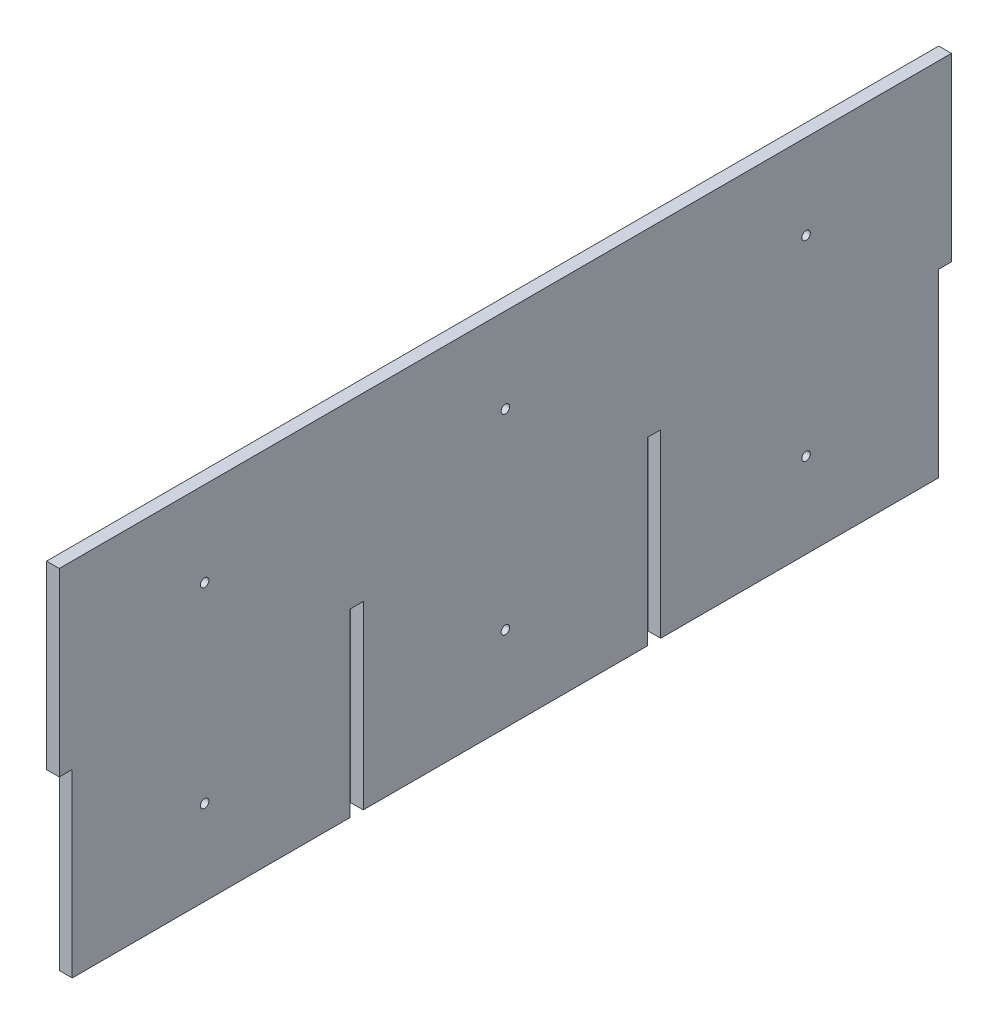
SolidWorks part; units mm, degrees
ref_plane "Front Plane" through (0, 0, 0) normal (0, 0, 1) x (1, 0, 0)
ref_plane "Top Plane" through (0, 0, 0) normal (0, 1, 0) x (1, 0, 0)
ref_plane "Right Plane" through (0, 0, 0) normal (1, 0, 0) x (0, 0, -1)
sketch "Sketch3" plane through (0, 0, 0) normal (1, 0, 0) x (0, 0, -1)
  line L1 (230.9117, 76.9159) -> (650.9117, 76.9159)
  line L2 (230.9117, 76.9159) -> (230.9117, 246.9159)
  line L3 (230.9117, 246.9159) -> (650.9117, 246.9159)
  line L4 (650.9117, 76.9159) -> (650.9117, 246.9159)
  dimension "D1" = 170
  dimension "D2" = 420
extrude "Boss-Extrude2" add sketch "Sketch3" along normal blind 6
sketch "Sketch4" plane through (6, 0, 0) normal (1, 0, 0) x (0, 0, -1)
  line L0 (230.9117, 246.9159) -> (230.9117, 76.9159) construction
  line L1 (230.9117, 161.9159) -> (237.0117, 161.9159)
  line L2 (230.9117, 161.9159) -> (230.9117, 76.9159)
  line L3 (230.9117, 76.9159) -> (237.0117, 76.9159)
  line L4 (237.0117, 161.9159) -> (237.0117, 76.9159)
  line L5 (230.9117, 76.9159) -> (650.9117, 76.9159) construction
  line L6 (650.9117, 76.9159) -> (650.9117, 246.9159) construction
  line L7 (650.9117, 161.9159) -> (644.8117, 161.9159)
  line L8 (650.9117, 161.9159) -> (650.9117, 76.9159)
  line L9 (650.9117, 76.9159) -> (644.8117, 76.9159)
  line L10 (644.8117, 161.9159) -> (644.8117, 76.9159)
  line L11 (650.9117, 246.9159) -> (230.9117, 246.9159) construction
  line L12 (367.8117, 246.9159) -> (374.0117, 246.9159)
  line L13 (367.8117, 246.9159) -> (367.8117, 161.9159)
  line L14 (367.8117, 161.9159) -> (374.0117, 161.9159)
  line L15 (374.0117, 246.9159) -> (374.0117, 161.9159)
  line L17 (514.0117, 246.9159) -> (507.8117, 246.9159)
  line L18 (514.0117, 246.9159) -> (514.0117, 161.9159)
  line L19 (514.0117, 161.9159) -> (507.8117, 161.9159)
  line L20 (507.8117, 246.9159) -> (507.8117, 161.9159)
  point P24 (370.9117, 246.9159)
  point P25 (510.9117, 246.9159)
  dimension "D1" = 6.1
  dimension "D2" = 6.1
  dimension "D3" = 140
  dimension "D4" = 140
  dimension "D5" = 6.2
  dimension "D6" = 6.2
extrude "Cut-Extrude1" cut sketch "Sketch4" against normal blind 6
sketch "Sketch5" plane through (6, 0, 0) normal (1, 0, 0) x (0, 0, -1)
  line L0 (367.8117, 246.9159) -> (230.9117, 246.9159) construction
  line L1 (237.0117, 76.9159) -> (644.8117, 76.9159) construction
  line L2 (507.8117, 246.9159) -> (374.0117, 246.9159) construction
  line L3 (650.9117, 246.9159) -> (514.0117, 246.9159) construction
  circle A0 centre (299.3617, 206.9159) radius 2
  circle A1 centre (299.3617, 116.9159) radius 2
  circle A2 centre (440.9117, 206.9159) radius 2
  circle A3 centre (582.4617, 206.9159) radius 2
  circle A4 centre (582.4617, 116.9159) radius 2
  circle A5 centre (440.9117, 116.9159) radius 2
  dimension "D7" = 4
  dimension "D8" = 4
  dimension "D9" = 4
  dimension "D10" = 4
  dimension "D11" = 4
  dimension "D12" = 4
  dimension "D1" = 40
  dimension "D2" = 40
  dimension "D3" = 40
  dimension "D4" = 40
  dimension "D5" = 40
  dimension "D6" = 40
extrude "Cut-Extrude2" cut sketch "Sketch5" against normal blind 6
sketch "Sketch6" plane through (0, 76.9159, 0) normal (0, -1, 0) x (1, 0, 0)
  line L0 (6, -237.0117) -> (6, -644.8117) construction
  line L1 (6, -250.9117) -> (0, -250.9117)
  line L2 (6, -250.9117) -> (6, -630.9117)
  line L3 (6, -630.9117) -> (0, -630.9117)
  line L4 (0, -250.9117) -> (0, -630.9117)
  line L5 (0, -237.0117) -> (0, -644.8117) construction
  dimension "D1" = 20
  dimension "D2" = 20
extrude "Boss-Extrude3" add sketch "Sketch6" along normal blind 30
sketch "Sketch7" plane through (0, 46.9159, 0) normal (0, -1, 0) x (1, 0, 0)
  line L1 (6, -250.9117) -> (0, -250.9117)
  line L2 (6, -250.9117) -> (6, -630.9117)
  line L3 (6, -630.9117) -> (0, -630.9117)
  line L4 (0, -250.9117) -> (0, -630.9117)
extrude "Cut-Extrude3" cut sketch "Sketch7" against normal blind 2
sketch "Sketch8" plane through (0, 246.9159, 0) normal (0, 1, 0) x (1, 0, 0)
  line L0 (0, 367.8117) -> (0, 230.9117) construction
  line L1 (6, 367.8117) -> (0, 367.8117)
  line L2 (6, 367.8117) -> (6, 250.9117)
  line L3 (6, 250.9117) -> (0, 250.9117)
  line L4 (0, 367.8117) -> (0, 250.9117)
  line L5 (0, 650.9117) -> (0, 514.0117) construction
  line L6 (6, 514.0117) -> (0, 514.0117)
  line L7 (6, 514.0117) -> (6, 630.9117)
  line L8 (6, 630.9117) -> (0, 630.9117)
  line L9 (0, 514.0117) -> (0, 630.9117)
  line L10 (0, 507.8117) -> (0, 374.0117) construction
  line L11 (6, 507.8117) -> (0, 507.8117)
  line L12 (6, 507.8117) -> (6, 374.0117)
  line L13 (6, 374.0117) -> (0, 374.0117)
  line L14 (0, 507.8117) -> (0, 374.0117)
  dimension "D1" = 20
  dimension "D2" = 20
extrude "Boss-Extrude4" add sketch "Sketch8" along normal blind 28
sketch "Sketch9" plane through (0, 161.9159, 0) normal (0, 1, 0) x (1, 0, 0)
  line L1 (6, 367.8117) -> (0, 367.8117)
  line L2 (6, 367.8117) -> (6, 374.0117)
  line L3 (6, 374.0117) -> (0, 374.0117)
  line L4 (0, 367.8117) -> (0, 374.0117)
extrude "Boss-Extrude5" add sketch "Sketch9" along normal blind 113
sketch "Sketch10" plane through (0, 161.9159, 0) normal (0, 1, 0) x (1, 0, 0)
  line L1 (6, 507.8117) -> (0, 507.8117)
  line L2 (6, 507.8117) -> (6, 514.0117)
  line L3 (6, 514.0117) -> (0, 514.0117)
  line L4 (0, 507.8117) -> (0, 514.0117)
extrude "Boss-Extrude6" add sketch "Sketch10" along normal blind 113
sketch "Sketch11" plane through (6, 0, 0) normal (1, 0, 0) x (0, 0, -1)
  line L0 (630.9117, 48.9159) -> (250.9117, 48.9159) construction
  line L1 (367.8117, 48.9159) -> (374.0117, 48.9159)
  line L2 (367.8117, 48.9159) -> (367.8117, 161.9159)
  line L3 (367.8117, 161.9159) -> (374.0117, 161.9159)
  line L4 (374.0117, 48.9159) -> (374.0117, 161.9159)
  line L6 (507.8117, 48.9159) -> (514.0117, 48.9159)
  line L7 (507.8117, 48.9159) -> (507.8117, 161.9159)
  line L8 (507.8117, 161.9159) -> (514.0117, 161.9159)
  line L9 (514.0117, 48.9159) -> (514.0117, 161.9159)
  dimension "D1" = 6.2
  dimension "D2" = 6.2
  dimension "D3" = 143.1
  dimension "D4" = 140
extrude "Cut-Extrude4" cut sketch "Sketch11" against normal blind 113
sketch "Sketch13" plane through (0, 0, -250.9117) normal (0, 0, 1) x (1, 0, 0)
  line L1 (0, 274.9159) -> (6, 274.9159)
  line L2 (0, 274.9159) -> (0, 246.9159)
  line L3 (0, 246.9159) -> (6, 246.9159)
  line L4 (6, 274.9159) -> (6, 246.9159)
  line L5 (0, 76.9159) -> (6, 76.9159)
  line L6 (0, 76.9159) -> (0, 48.9159)
  line L7 (0, 48.9159) -> (6, 48.9159)
  line L8 (6, 76.9159) -> (6, 48.9159)
extrude "Cut-Extrude5" cut sketch "Sketch13" against normal blind 1000
